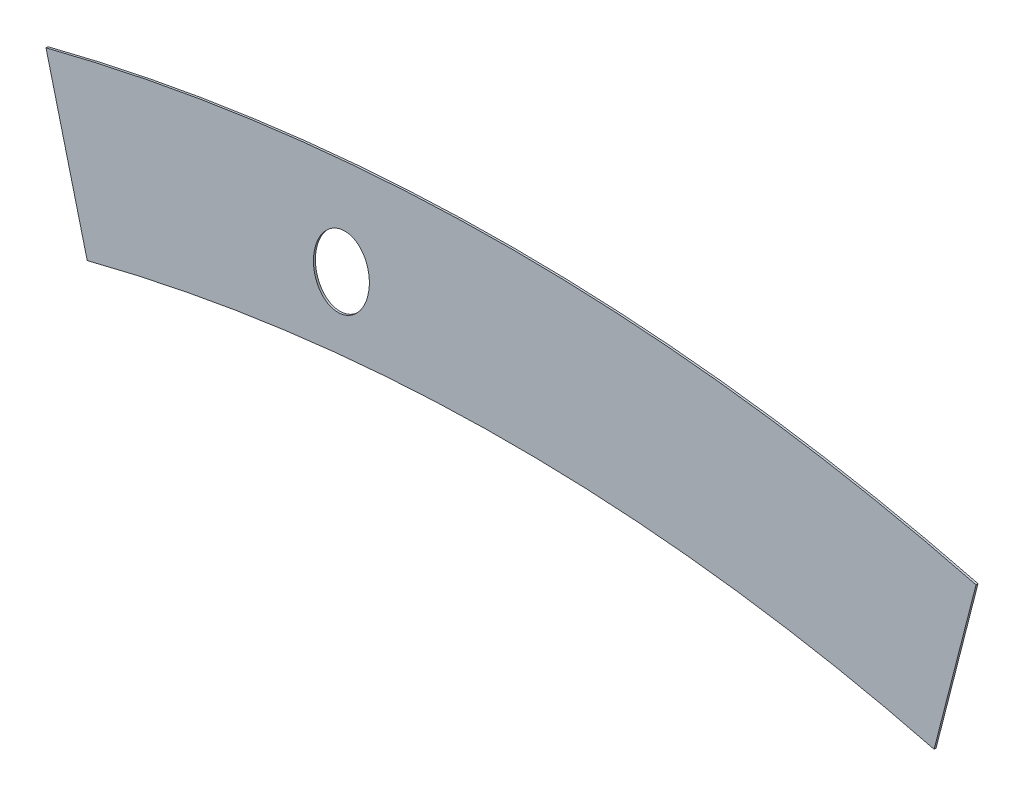
SolidWorks part; units mm, degrees
material "6061 Alloy"
ref_plane "front" through (0, 0, 0) normal (0, 0, 1) x (1, 0, 0)
ref_plane "top" through (0, 0, 0) normal (0, 1, 0) x (1, 0, 0)
ref_plane "right" through (0, 0, 0) normal (1, 0, 0) x (0, 0, -1)
sketch "Sketch1" plane through (0, 0, 0) normal (0, 0, 1) x (1, 0, 0)
  line L0 (0, 0) -> (0, -273.05) construction
  line L1 (0, 0) -> (383.281, 0) construction
  line L2 (-752.475, -94.9751) -> (-685.8, -359.7625)
  line L3 (752.475, -94.9751) -> (684.6062, -359.456)
  line L4 (-241.3, -9.6287) -> (-299.2267, -289.3462) construction
  arc A0 (752.475, -94.9751) -> (-752.475, -94.9751) centre (0, -3028.3658) ccw
  arc A1 (684.6062, -359.456) -> (-685.8, -359.7625) centre (0, -3028.3658) ccw
  ellipse E0 centre (-274.4583, -169.7439) end of major axis (-286.6914, -228.8155) minor radius 44.45
  dimension "D1" = 3028.3658
  dimension "D5" = 11.7
  dimension "D7" = 88.9
  dimension "D12" = 103.1875
  dimension "D2" = 1504.95
  dimension "D3" = 273.05
  dimension "D4" = 685.8
  dimension "D6" = 241.3
  dimension "D8" = 120.65
  dimension "D9" = 163.5125
  dimension "D10" = 752.475
  dimension "D11" = 299.2267
  dimension "D13" = 684.6062
extrude "Base-Extrude" add sketch "Sketch1" against normal blind 3.175
